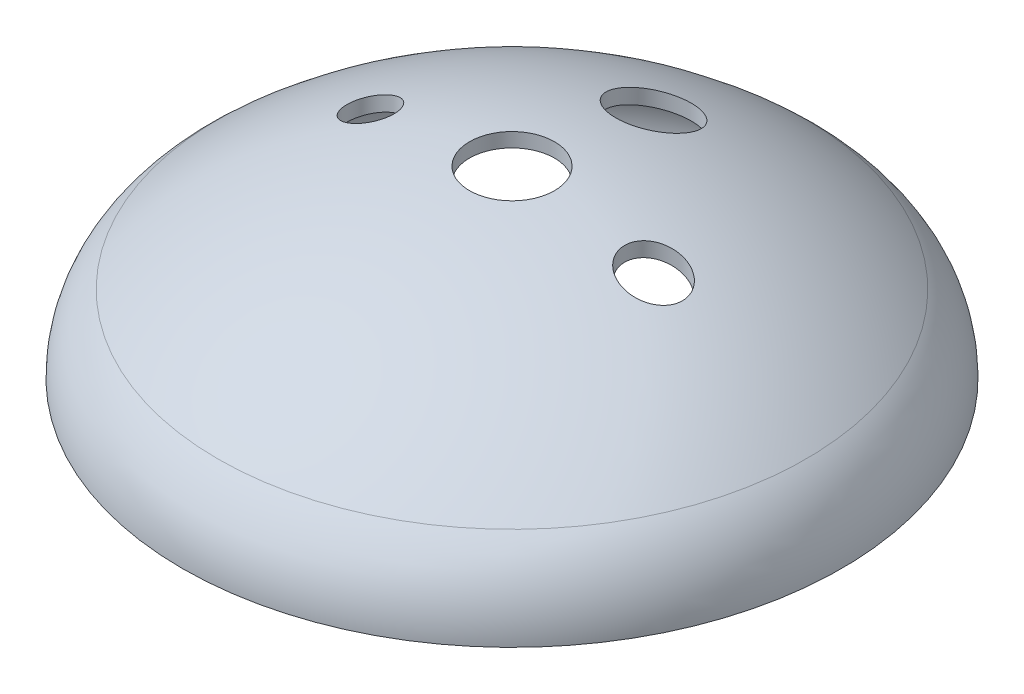
SolidWorks part; units mm, degrees
material "АД0 ГОСТ 4784-97"
ref_plane "Спереди" through (0, 0, 0) normal (0, 0, 1) x (1, 0, 0)
ref_plane "Сверху" through (0, 0, 0) normal (0, 1, 0) x (1, 0, 0)
ref_plane "Справа" through (0, 0, 0) normal (1, 0, 0) x (0, 0, -1)
sketch "Эскиз1" plane through (0, 0, 0) normal (0, 0, 1) x (1, 0, 0)
  line L0 (0, 39.365) -> (0, 36.365)
  line L1 (66.85, 0) -> (69.85, 0)
  line L2 (0, 69.552) -> (0, 0) construction
  arc A0 (0, 39.365) -> (62.3196, 16.3495) centre (0, -56.515) cw
  arc A1 (0, 36.365) -> (60.3697, 14.0697) centre (0, -56.515) cw
  arc A2 (60.3697, 14.0697) -> (66.85, 0) centre (48.3362, 0) cw
  arc A3 (62.3196, 16.3495) -> (69.85, 0) centre (48.3362, 0) cw
revolve "Повернуть1" add sketch "Эскиз1" angle 360 about L2
ref_plane "Плоскость1" through (0, 39.365, 0) normal (0, 1, 0) x (1, 0, 0)
sketch "Эскиз2" plane through (0, 39.365, 0) normal (0, 1, 0) x (1, 0, 0)
  circle A0 centre (0, 0) radius 9
  circle A3 centre (0, 0) radius 30 construction
  circle A4 centre (-30, 0) radius 5
  circle A7 centre (0, 30) radius 8
  circle A8 centre (30, 0) radius 6.125
  dimension "D1" = 18
  dimension "D2" = 60
  dimension "D3" = 10
  dimension "D4" = 12.25
  dimension "D5" = 16
extrude "Вырез-Вытянуть1" cut sketch "Эскиз2" against normal through all
